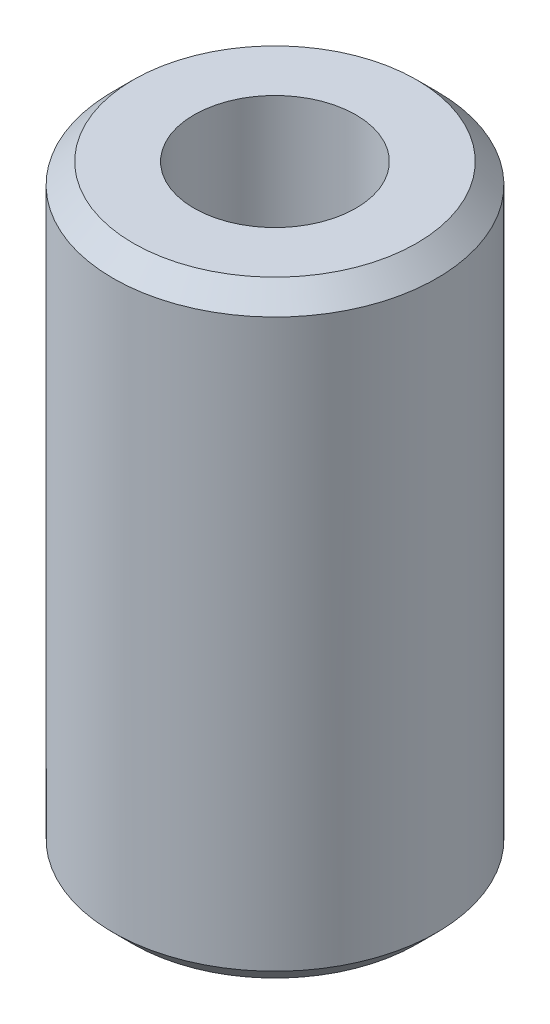
SolidWorks part; units mm, degrees
ref_plane "Плоскость1" through (0, 0, 0) normal (0, 0, 1) x (1, 0, 0)
ref_plane "Плоскость2" through (0, 0, 0) normal (0, 1, 0) x (1, 0, 0)
ref_plane "Плоскость3" through (0, 0, 0) normal (1, 0, 0) x (0, 0, -1)
sketch "Эскиз1" plane through (0, 0, 0) normal (0, 0, 1) x (1, 0, 0)
  line L0 (0, 0) -> (0, 93.2295) construction
  line L1 (8, 0) -> (8, 30)
  line L2 (8, 0) -> (4, 0)
  line L3 (4, 0) -> (4, 10)
  line L4 (4, 10) -> (1, 13)
  line L5 (1, 13) -> (1, 17)
  line L6 (1, 17) -> (4, 20)
  line L7 (4, 20) -> (4, 30)
  line L8 (4, 30) -> (8, 30)
  dimension "D1" = 30
  dimension "D2" = 16
  dimension "D3" = 8
  dimension "D4" = 8
  dimension "D5" = 2
  dimension "D6" = 45
  dimension "D7" = 10
  dimension "D8" = 10
revolve "Повернуть1" add sketch "Эскиз1" angle 360 about L0
cosmetic thread "Условное изображение резьбы1" parameters "D1"=12, "D2"=14.5
chamfer "Фаска1" distance 1 angle 45 2 edges at (0, 30, -8) (0, 0, -8)
